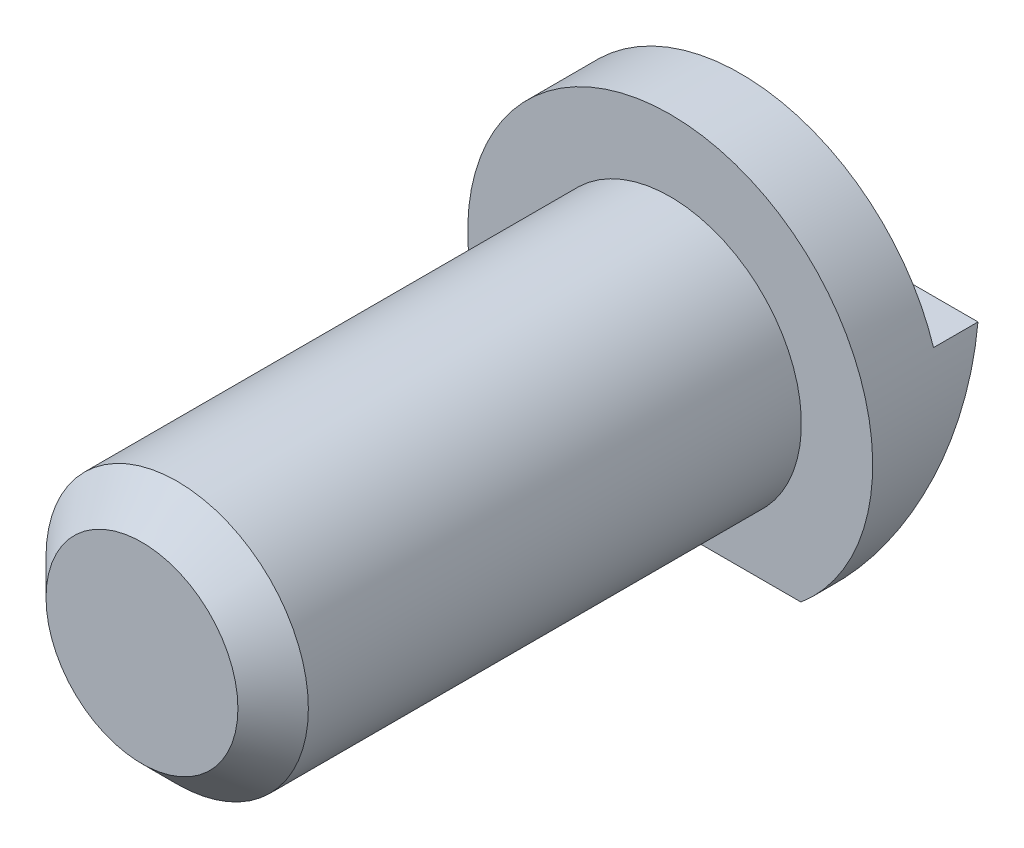
SolidWorks part; units mm, degrees
ref_plane "정면" through (0, 0, 0) normal (0, 0, 1) x (1, 0, 0)
ref_plane "윗면" through (0, 0, 0) normal (0, 1, 0) x (1, 0, 0)
ref_plane "우측면" through (0, 0, 0) normal (1, 0, 0) x (0, 0, -1)
sketch "스케치1" plane through (0, 0, 0) normal (0, 0, 1) x (1, 0, 0)
  circle A0 centre (0, 0) radius 3.725
  dimension "D1" = 7.45
extrude "보스-돌출1" add sketch "스케치1" along normal blind 15
sketch "스케치2" plane through (0, 0, 0) normal (0, 0, -1) x (-1, 0, 0)
  line L0 (-3.7135, -4.39) -> (3.7135, -4.39)
  circle A0 centre (0, 0) radius 5.75
  point P5 (0, -4.39)
  point P6 (0, -5.75)
  circle M1 centre (0, 0) radius 3.725
  dimension "D1" = 11.5
  dimension "D2" = 1.36
extrude "보스-돌출2" add sketch "스케치2" along normal blind 5 contours L0 A0 M1 | M1
chamfer "모따기2" distance 1 angle 45 1 edges at (3.725, 0, 15)
chamfer "모따기3" distance 4.5 distance2 10 1 edges at (0, -4.39, -5)
sketch "스케치3" plane through (0, 0, -5) normal (0, 0, -1) x (-1, 0, 0)
  line L0 (-5.4772, 1.75) -> (5.4772, 1.75)
  circle A0 centre (0, 0) radius 5.75
  point P5 (0, 5.75)
  point P6 (0, 1.75)
  arc M1 (1.2611, 5.61) -> (-1.2611, 5.61) centre (0, 0) ccw
  line M2 (-1.2611, 5.61) -> (1.2611, 5.61)
  dimension "D2" = 11.5
  dimension "D1" = 4
extrude "컷-돌출1" cut sketch "스케치3" against normal blind 3 contours L0 A0 M2 | M2 M1
